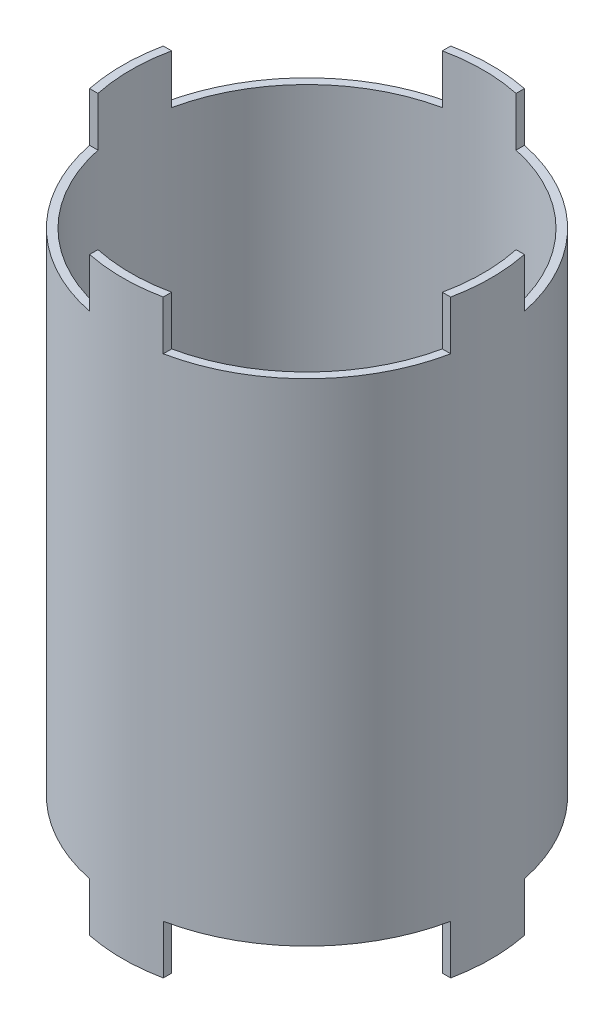
SolidWorks part; units mm, degrees
ref_plane "Front Plane" through (0, 0, 0) normal (0, 0, 1) x (1, 0, 0)
ref_plane "Top Plane" through (0, 0, 0) normal (0, 1, 0) x (1, 0, 0)
ref_plane "Right Plane" through (0, 0, 0) normal (1, 0, 0) x (0, 0, -1)
sketch "Sketch1" plane through (0, 0, 0) normal (0, 1, 0) x (1, 0, 0)
  circle A0 centre (0, 0) radius 57.15
  circle A1 centre (0, 0) radius 54.61
  dimension "D1" = 114.3
  dimension "D2" = 2.54
extrude "Boss-Extrude1" add sketch "Sketch1" along normal blind 152.4
sketch "Sketch2" plane through (0, 152.4, 0) normal (0, 1, 0) x (1, 0, 0)
  line L0 (-55.9953, 11.43) -> (-53.4004, 11.43)
  line L1 (-53.4004, -11.43) -> (-55.9953, -11.43)
  line L2 (11.43, 53.4004) -> (11.43, 55.9953)
  line L3 (-11.43, 53.4004) -> (-11.43, 55.9953)
  line L4 (53.4004, 11.43) -> (55.9953, 11.43)
  line L5 (53.4004, -11.43) -> (55.9953, -11.43)
  line L6 (11.43, -53.4004) -> (11.43, -55.9953)
  line L7 (-11.43, -53.4004) -> (-11.43, -55.9953)
  line L8 (11.43, -53.4004) -> (11.4137, -55.9987)
  arc A0 (-55.9953, -11.43) -> (-55.9953, 11.43) centre (0, 0) cw
  arc A1 (-11.43, 53.4004) -> (11.43, 53.4004) centre (0, 0) cw
  circle A2 centre (0, 0) radius 57.15 construction
  arc A3 (-53.4004, 11.43) -> (-53.4004, -11.43) centre (0, 0) ccw
  circle A4 centre (0, 0) radius 54.61 construction
  arc A5 (-11.43, 55.9953) -> (11.43, 55.9953) centre (0, 0) cw
  arc A6 (53.4004, 11.43) -> (53.4004, -11.43) centre (0, 0) cw
  arc A7 (55.9953, 11.43) -> (55.9953, -11.43) centre (0, 0) cw
  arc A8 (-11.43, -53.4004) -> (11.43, -53.4004) centre (0, 0) ccw
  arc A9 (-11.43, -55.9953) -> (11.4137, -55.9987) centre (0, 0) ccw
  dimension "D1" = 11.43
  dimension "D9" = 11.43
  dimension "D2" = 22.86
  dimension "D3" = 11.43
  dimension "D4" = 22.86
  dimension "D5" = 11.43
  dimension "D6" = 22.86
  dimension "D7" = 11.43
  dimension "D8" = 22.86
  dimension "D10" = 22.86
  dimension "D11" = 11.43
  dimension "D12" = 22.86
  dimension "D13" = 11.43
  dimension "D14" = 22.86
  dimension "D15" = 11.43
  dimension "D16" = 22.86
extrude "Boss-Extrude2" add sketch "Sketch2" along normal blind 15.24 contours A3 L1 A0 L0 | A1 L2 A5 L3 | A7 L5 A6 L4 | L8 A9 L7 A8
sketch "Sketch3" plane through (0, 0, 0) normal (0, -1, 0) x (1, 0, 0)
  line L10 (11.43, 55.9953) -> (11.43, 53.4004)
  line L11 (-11.43, 53.4004) -> (-11.43, 55.9953)
  line L12 (53.4004, 11.43) -> (55.9953, 11.43)
  line L13 (53.4004, -11.43) -> (55.9953, -11.43)
  line L14 (-11.43, -53.4004) -> (-11.43, -55.9953)
  line L15 (11.43, -53.4004) -> (11.43, -55.9953)
  line L16 (-55.9953, 11.43) -> (-53.4004, 11.43)
  line L17 (-55.9953, -11.43) -> (-53.4004, -11.43)
  arc A10 (-53.4004, 11.43) -> (-53.4004, -11.43) centre (0, 0) ccw
  circle A11 centre (0, 0) radius 54.61 construction
  arc A12 (-55.9953, 11.43) -> (-55.9953, -11.43) centre (0, 0) ccw
  circle A13 centre (0, 0) radius 57.15 construction
  arc A14 (-11.43, -53.4004) -> (11.43, -53.4004) centre (0, 0) ccw
  arc A15 (11.43, -55.9953) -> (-11.43, -55.9953) centre (0, 0) cw
  arc A16 (53.4004, -11.43) -> (53.4004, 11.43) centre (0, 0) ccw
  arc A17 (55.9953, -11.43) -> (55.9953, 11.43) centre (0, 0) ccw
  arc A18 (-11.43, 53.4004) -> (11.43, 53.4004) centre (0, 0) cw
  arc A19 (-11.43, 55.9953) -> (11.43, 55.9953) centre (0, 0) cw
  dimension "D1" = 11.43
  dimension "D7" = 22.86
  dimension "D2" = 11.43
  dimension "D3" = 22.86
  dimension "D4" = 22.86
  dimension "D5" = 11.43
  dimension "D6" = 11.43
  dimension "D8" = 11.43
  dimension "D9" = 11.43
  dimension "D10" = 22.86
  dimension "D11" = 22.86
  dimension "D12" = 11.43
  dimension "D13" = 11.43
  dimension "D14" = 22.86
  dimension "D15" = 22.86
extrude "Boss-Extrude3" add sketch "Sketch3" along normal blind 15.24 contours A15 L14 A14 L15 | A12 L17 A10 L16 | A17 L12 A16 L13 | A19 L10 A18 L11
equation "\"MDF\"= .3"
equation "\"Foamcore\"= .1"
equation "\"GMaterial\"= .6"
equation "\"D1@Boss-Extrude2\"=\"GMaterial\""
equation "\"D1@Boss-Extrude3\"=\"GMaterial\""
